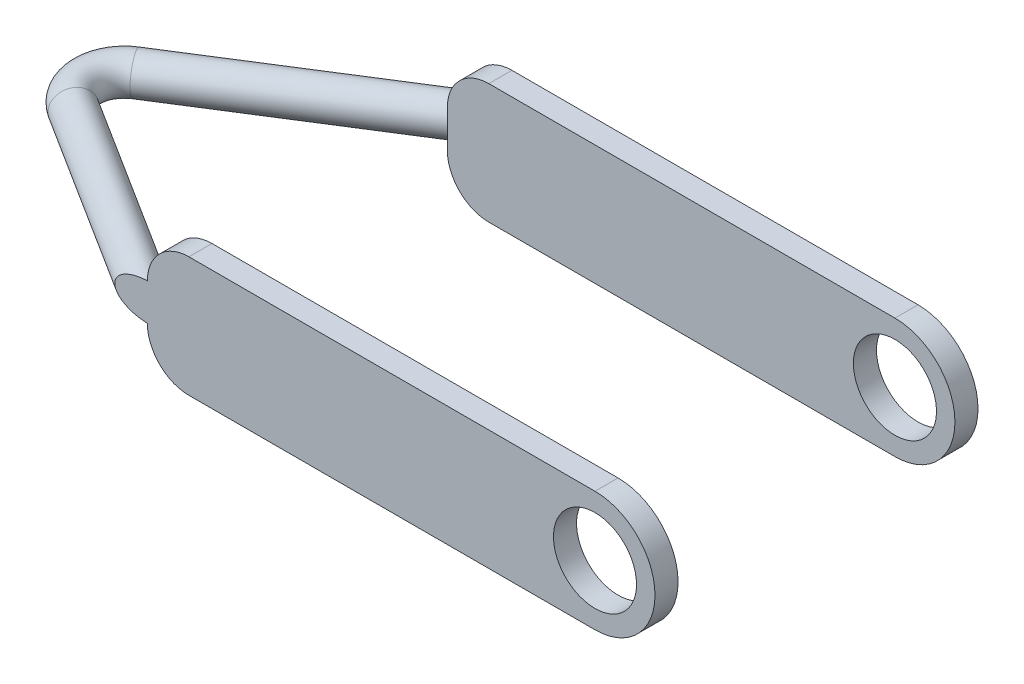
SolidWorks part; units mm, degrees
ref_plane "Front Plane" through (0, 0, 0) normal (0, 0, 1) x (1, 0, 0)
ref_plane "Top Plane" through (0, 0, 0) normal (0, 1, 0) x (1, 0, 0)
ref_plane "Right Plane" through (0, 0, 0) normal (1, 0, 0) x (0, 0, -1)
sketch "Sketch1" plane through (0, 0, 0) normal (0, 1, 0) x (1, 0, 0)
  line L2 (52.3892, -40.0309) -> (-0.2726, -6.7635)
  arc A5 (-4, 0) -> (-0.2726, -6.7635) centre (4, 0) ccw
sketch "Sketch2" plane through (0, 0, 0) normal (0, 0, 1) x (1, 0, 0)
  line L0 (-0.2726, 0) -> (-4, 0) construction
  circle A0 centre (-4, 0) radius 4
sweep "Sweep1" add profiles "Sketch2" path "Sketch1"
sketch "Sketch4" plane through (0, 0, 0) normal (0, 1, 0) x (1, 0, 0)
  line L0 (0, 0) -> (44, 0)
  line L1 (44, 0) -> (44, -30)
  line L2 (54.5255, -36.6492) -> (1.8637, -3.3817) construction
  line L3 (44, -30) -> (57.1771, -30)
  line L4 (57.1771, -30) -> (57.1771, -46.5317)
  line L5 (57.1771, -46.5317) -> (44, -46.5317)
  line L6 (44, -30) -> (44, -35)
  line L7 (44, -35) -> (34.5973, -35)
  line L8 (34.5973, -35) -> (44, -46.5317)
extrude "Cut-Extrude1" cut sketch "Sketch4" against normal mid plane 20 contours L7 L8 L5 L4 L3 L6
sketch "Sketch5" plane through (0, 0, 0) normal (0, 1, 0) x (1, 0, 0)
  line L0 (44, -35) -> (154, -35)
  line L1 (154, -35) -> (154, -30)
  line L2 (154, -30) -> (44, -30)
  line L3 (44, -35) -> (44, -30) construction
  line L4 (44, -30) -> (1.8637, -3.3817) construction
  line L5 (44, -30) -> (44, -35)
extrude "Boss-Extrude1" add sketch "Sketch5" along normal mid plane 26
sketch "Sketch6" plane through (0, 0, 35) normal (0, 0, 1) x (1, 0, 0)
  line L0 (44, 3.9935) -> (44, 4)
  line L1 (53, 13) -> (53.01, 13)
  line L2 (44, 13) -> (154, 13) construction
  line L6 (53, 13) -> (52.7784, 14.2642)
  line L7 (52.7784, 14.2642) -> (42.6067, 14.2642)
  line L8 (42.6067, 14.2642) -> (42.8483, 6.726)
  line L9 (42.8483, 6.726) -> (44, 4)
  circle A2 centre (141, 0) radius 9
  arc A4 (44, 4) -> (53, 13) centre (53, 4) cw
  point P12 (44, 13)
  dimension "D1" = 9
extrude "Cut-Extrude2" cut sketch "Sketch6" against normal mid plane 26
sketch "Sketch7" plane through (0, 0, 35) normal (0, 0, 1) x (1, 0, 0)
  line L1 (141, -13) -> (141, -15.8595)
  line L2 (141, -15.8595) -> (158.3678, -15.8595)
  line L3 (158.3678, -15.8595) -> (158.3678, 15.9887)
  line L4 (158.3678, 15.9887) -> (141, 15.9887)
  line L5 (141, 15.9887) -> (141, 13)
  line L6 (44, -3.9935) -> (44, -4)
  line L7 (53, -13) -> (53.01, -13)
  line L8 (44, -13) -> (154, -13) construction
  line L12 (53, -13) -> (53, -14.7129)
  line L13 (53, -14.7129) -> (42.0603, -14.7129)
  line L14 (42.0603, -14.7129) -> (44, -4)
  arc A1 (141, -13) -> (141, 13) centre (141, 0) ccw
  arc A2 (44, -4) -> (53, -13) centre (53, -4) ccw
  point P17 (44, -13)
  line M8 (154, 13) -> (53, 13)
  line M12 (44, -3.9935) -> (44, -13)
  line M13 (44, -13) -> (154, -13)
  line M14 (154, -13) -> (154, 13)
  dimension "D1" = 9
extrude "Cut-Extrude3" cut sketch "Sketch7" against normal blind 10 contours A2 M12 M13 | A1 M13 M14 | A1 M14 M8
mirror "Mirror1" about plane through (-4, 0, 0) normal (0, 0, 1) of "Cut-Extrude1", "Sweep1", "Boss-Extrude1", "Cut-Extrude2", "Cut-Extrude3"
sketch "Sketch8" plane through (0, 0, 0) normal (0, 1, 0) x (1, 0, 0)
  line L0 (0, 0) -> (4, 0)
